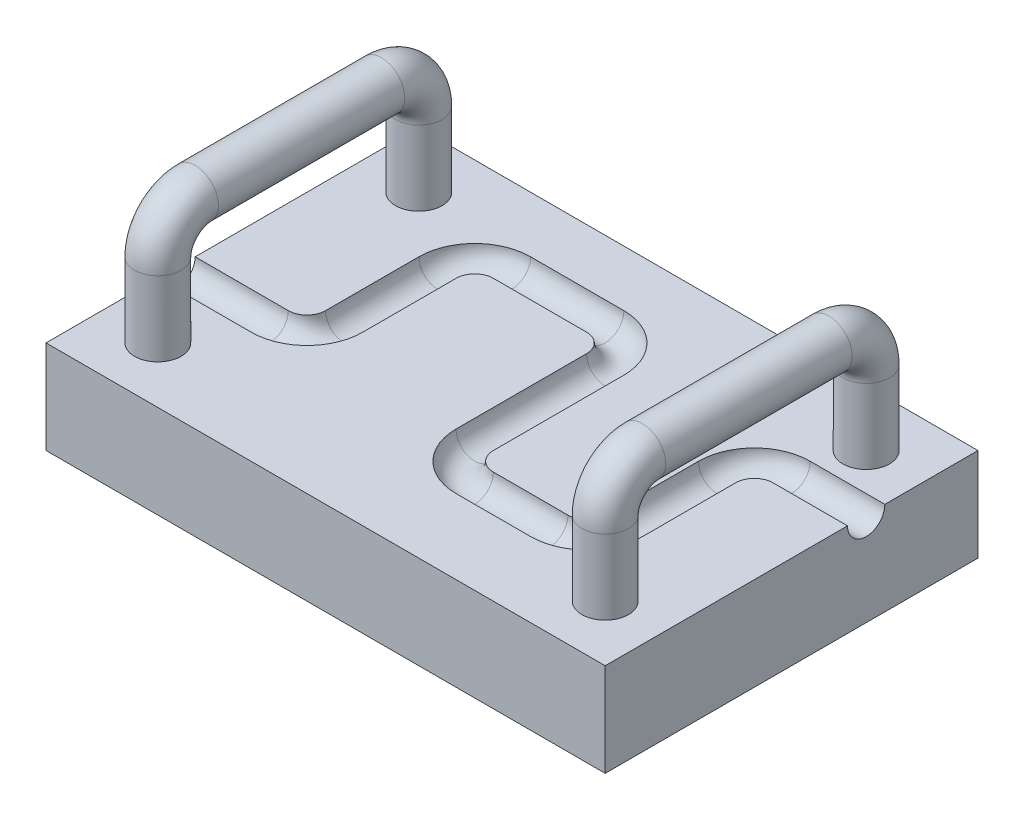
SolidWorks part; units mm, degrees
ref_plane "Front Plane" through (0, 0, 0) normal (0, 0, 1) x (1, 0, 0)
ref_plane "Top Plane" through (0, 0, 0) normal (0, 1, 0) x (1, 0, 0)
ref_plane "Right Plane" through (0, 0, 0) normal (1, 0, 0) x (0, 0, -1)
sketch "Sketch1" plane through (0, 0, 0) normal (0, 1, 0) x (1, 0, 0)
  line L1 (-150, -100) -> (150, -100)
  line L2 (-150, -100) -> (-150, 100)
  line L3 (-150, 100) -> (150, 100)
  line L4 (150, -100) -> (150, 100)
  line L5 (-150, -100) -> (150, 100) construction
  line L6 (-150, 100) -> (150, -100) construction
  point P0 (0, 0)
  dimension "D1" = 300
  dimension "D2" = 200
extrude "Boss-Extrude1" add sketch "Sketch1" along normal blind 50
sketch "Sketch2" plane through (0, 50, 0) normal (0, 1, 0) x (1, 0, 0)
  line L0 (150, 40) -> (110, 40)
  line L1 (150, -100) -> (150, 100) construction
  line L2 (90, 20) -> (90, -30)
  line L3 (70, -50) -> (30, -50)
  line L4 (10, -30) -> (10, 40)
  line L5 (-10, 60) -> (-60, 60)
  line L6 (-80, 40) -> (-80, -10)
  line L7 (-100, -30) -> (-150, -30)
  line L9 (150, 100) -> (-150, 100) construction
  line L10 (-150, 100) -> (-150, -100) construction
  arc A0 (110, 40) -> (90, 20) centre (110, 20) ccw
  arc A1 (90, -30) -> (70, -50) centre (70, -30) cw
  arc A2 (30, -50) -> (10, -30) centre (30, -30) cw
  arc A3 (10, 40) -> (-10, 60) centre (-10, 40) ccw
  arc A4 (-60, 60) -> (-80, 40) centre (-60, 40) ccw
  arc A5 (-80, -10) -> (-100, -30) centre (-100, -10) cw
  point P16 (90, 40)
  point P19 (90, -50)
  point P22 (10, -50)
  point P25 (10, 60)
  point P28 (-80, 60)
  point P31 (-80, -30)
  dimension "D8" = 20
  dimension "D1" = 60
  dimension "D2" = 60
  dimension "D3" = 90
  dimension "D4" = 80
  dimension "D5" = 110
  dimension "D6" = 90
  dimension "D7" = 90
sweep "Cut-Sweep1" cut path "Sketch2" circular profile diameter 20 parameters "D3"=20
sketch "Sketch14" plane through (0, 50, 0) normal (0, 1, 0) x (1, 0, 0)
  line L0 (-150, 100) -> (-150, -20) construction
  line L1 (150, 100) -> (-150, 100) construction
  circle A0 centre (-120, 70) radius 12.5
  dimension "D3" = 25
  dimension "D1" = 30
  dimension "D2" = 30
sketch3d "3DSketch1"
  line L0 (-120, 50, -70) -> (-120, 90, -70)
  line L1 (-120, 110, -50) -> (-120, 110, 50)
  line L2 (-120, 90, 70) -> (-120, 50, 70)
  line L3 (-150, 50, 100) -> (150, 50, 100) construction
  arc A0 (-120, 110, 50) -> (-120, 90, 70) centre (-120, 90, 50) ccw
  arc A1 (-120, 90, -70) -> (-120, 110, -50) centre (-120, 90, -50) ccw
  point P9 (-120, 110, 70)
  point P10 (-100, 90, 50)
  point P13 (-120, 110, -70)
  point P14 (-100, 90, -50)
  dimension "D4" = 20
  dimension "D1" = 30
  dimension "D2" = 60
  dimension "D3" = 60
sweep "Sweep1" add profiles "Sketch14" path "3DSketch1"
mirror "Mirror1" about plane through (0, 0, 0) normal (1, 0, 0) of "Sweep1"
